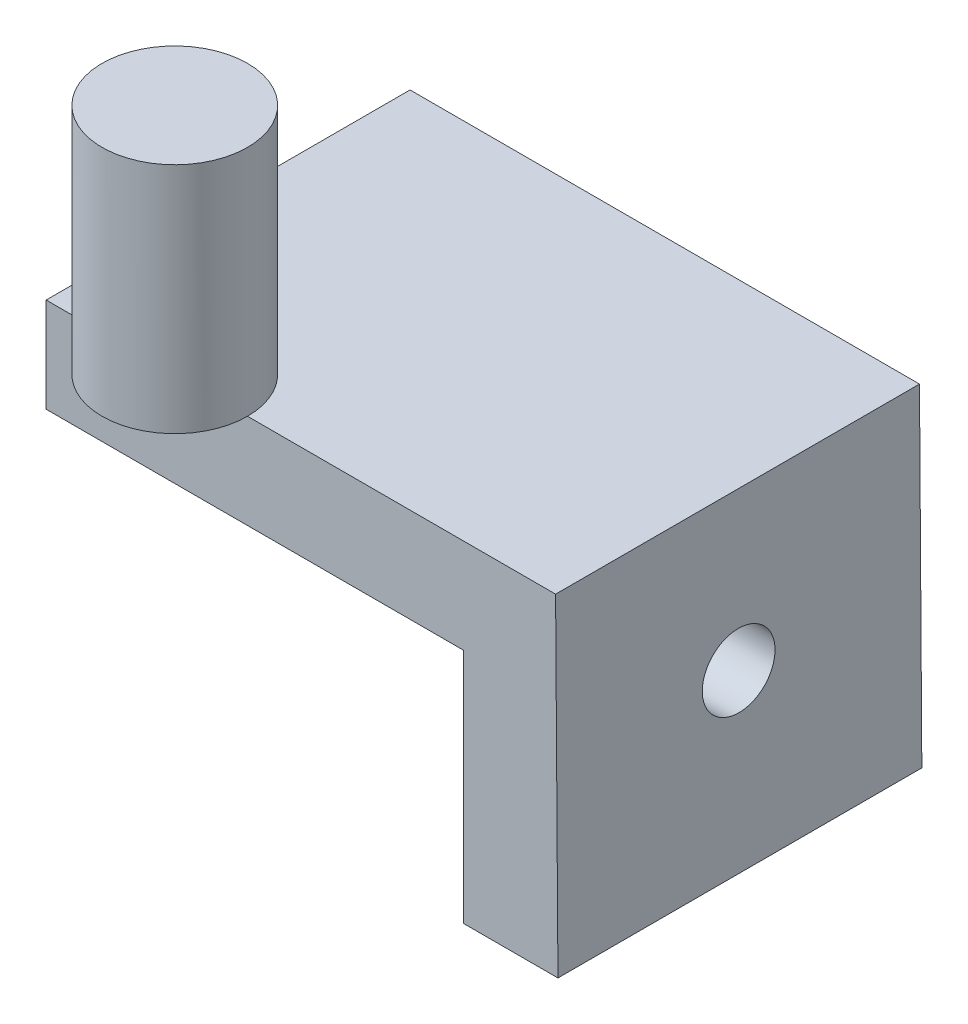
SolidWorks part; units mm, degrees
ref_plane "Alzado" through (0, 0, 0) normal (0, 0, 1) x (1, 0, 0)
ref_plane "Planta" through (0, 0, 0) normal (0, 1, 0) x (1, 0, 0)
ref_plane "Vista lateral" through (0, 0, 0) normal (1, 0, 0) x (0, 0, -1)
sketch "Croquis1" plane through (0, 0, 0) normal (0, 0, 1) x (1, 0, 0)
  line L0 (-35.1623, 0) -> (-0.1623, 0)
  line L1 (55, 0) -> (-55, 0) construction
  line L2 (-35.1623, 0) -> (-35.1623, -6.5)
  line L3 (-35.1623, -6.5) -> (-6.5, -6.5)
  line L4 (-6.5, -6.5) -> (-6.5, -22.7576)
  line L5 (-6.5, -22.7576) -> (0, -22.7576)
  line L6 (0, -55) -> (0, 55) construction
  line L7 (0, -22.7576) -> (-0.1623, 0)
  dimension "D1" = 35
  dimension "D2" = 6.5
  dimension "D3" = 6.5
extrude "Saliente-Extruir1" add sketch "Croquis1" along normal mid plane 25
sketch "Croquis3" plane through (0, 0, 0) normal (0, 1, 0) x (1, 0, 0)
  line L0 (-12.5167, 0) -> (12.5167, 0) construction
  line L1 (-19.6623, 0) -> (-20.6623, 0)
  line L2 (-19.6623, 0) -> (-19.6623, 5)
  line L3 (-19.6623, 5) -> (-20.6623, 5)
  line L4 (-20.6623, 0) -> (-20.6623, 5)
  line L5 (-20.1623, 0) -> (-20.1623, 0.9324) construction
  line L7 (-0.1623, -12.5) -> (-0.1623, 12.5) construction
  line L9 (-20.6623, 0) -> (-19.6623, 0)
  dimension "D1" = 5
  dimension "D2" = 1
  dimension "D3" = 20
sketch "Croquis5" plane through (-0.1623, -0.0012, 0) normal (1, 0.0071, 0) x (0, 0, -1)
  line L0 (0, 12.5167) -> (0, -12.5167) construction
  line L1 (-12.5, -22.757) -> (12.5, -22.757) construction
  circle A0 centre (0, -10.757) radius 2.5
  dimension "D1" = 5
  dimension "D2" = 12
extrude "Cortar-Extruir1" cut sketch "Croquis5" against normal blind 25
sketch "Croquis7" plane through (0, 0, 0) normal (0, 1, 0) x (1, 0, 0)
  line L0 (-20.1623, 0) -> (-20.1623, 5)
  line L1 (-19.6623, 5) -> (-20.6623, 5) construction
sketch "Croquis15" plane through (0, 0, 12.5) normal (0, 0, 1) x (1, 0, 0)
  line L0 (13.75, 0) -> (-13.75, 0) construction
  line L1 (-26.3263, 0) -> (-21.3263, 0)
  line L2 (-26.3263, 0) -> (-26.3263, 16)
  line L3 (-26.3263, 16) -> (-21.3263, 16)
  line L4 (-21.3263, 0) -> (-21.3263, 16)
  dimension "D1" = 16
  dimension "D2" = 5
revolve "Revolución2" add sketch "Croquis15" angle 360 about L2
